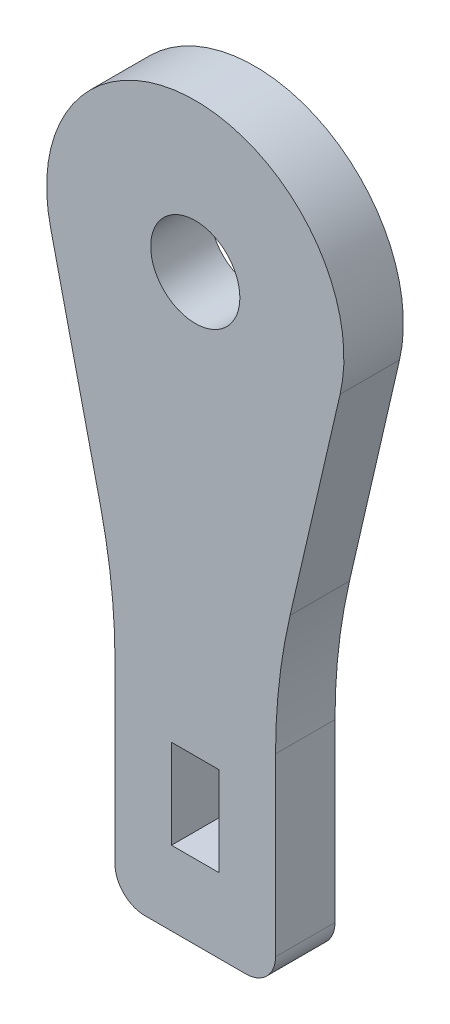
SolidWorks part; units mm, degrees
ref_plane "Front Plane" through (0, 0, 0) normal (0, 0, 1) x (1, 0, 0)
ref_plane "Top Plane" through (0, 0, 0) normal (0, 1, 0) x (1, 0, 0)
ref_plane "Right Plane" through (0, 0, 0) normal (1, 0, 0) x (0, 0, -1)
sketch "Sketch1" plane through (0, 0, 0) normal (0, 0, 1) x (1, 0, 0)
  line L0 (-55, 0) -> (-55, -86.9275) construction
  line L1 (-79.3579, -5.6295) -> (-70.941, -42.0481)
  line L2 (-68.5012, -63.4401) -> (-68.5012, -93)
  line L3 (-63.5012, -98) -> (-46.4988, -98)
  line L4 (-41.4988, -63.4401) -> (-41.4988, -93)
  line L5 (-30.6421, -5.6295) -> (-39.059, -42.0481)
  line L7 (-59, -70.5) -> (-51, -70.5)
  line L8 (-59, -70.5) -> (-59, -85.5)
  line L9 (-59, -85.5) -> (-51, -85.5)
  line L10 (-51, -70.5) -> (-51, -85.5)
  line L11 (-59, -70.5) -> (-51, -85.5) construction
  line L12 (-59, -85.5) -> (-51, -70.5) construction
  circle A0 centre (-55, 0) radius 7.5
  arc A1 (-30.6421, -5.6295) -> (-79.3579, -5.6295) centre (-55, 0) ccw
  arc A2 (-68.5012, -63.4401) -> (-70.941, -42.0481) centre (-163.5012, -63.4401) ccw
  arc A3 (-41.4988, -63.4401) -> (-39.059, -42.0481) centre (53.5012, -63.4401) cw
  arc A4 (-41.4988, -93) -> (-46.4988, -98) centre (-46.4988, -93) cw
  arc A5 (-63.5012, -98) -> (-68.5012, -93) centre (-63.5012, -93) cw
  point P3 (-55, -78)
  point P12 (-55, -98)
  point P22 (-41.4988, -98)
  point P25 (-68.5012, -98)
  dimension "D1" = 95
  dimension "D2" = 25
  dimension "D7" = 5
  dimension "D3" = 98
  dimension "D4" = 15
  dimension "D5" = 8
  dimension "D6" = 20
extrude "Boss-Extrude1" add sketch "Sketch1" along normal blind 10
